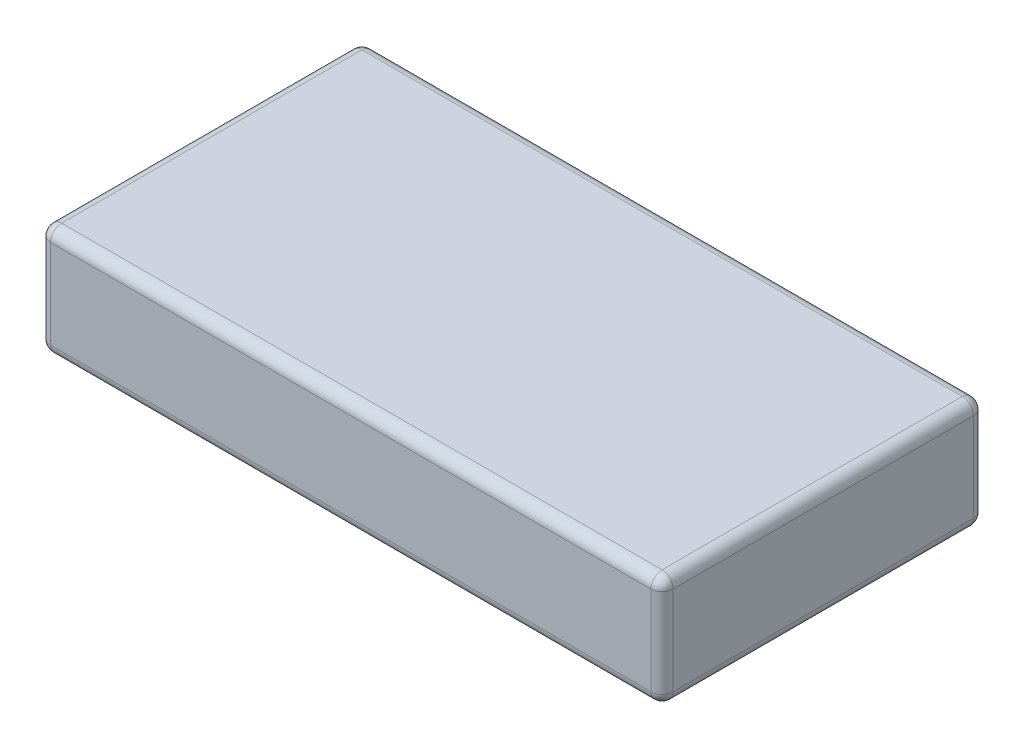
SolidWorks part; units mm, degrees
ref_plane "前视基准面" through (0, 0, 0) normal (0, 0, 1) x (1, 0, 0)
ref_plane "上视基准面" through (0, 0, 0) normal (0, 1, 0) x (1, 0, 0)
ref_plane "右视基准面" through (0, 0, 0) normal (1, 0, 0) x (0, 0, -1)
sketch "草图1" plane through (0, 0, 0) normal (0, 1, 0) x (1, 0, 0)
  line L1 (-28, 14.5) -> (28, 14.5)
  line L2 (-28, 14.5) -> (-28, -14.5)
  line L3 (-28, -14.5) -> (28, -14.5)
  line L4 (28, 14.5) -> (28, -14.5)
  line L5 (-28, 14.5) -> (28, -14.5) construction
  line L6 (-28, -14.5) -> (28, 14.5) construction
  point P1 (0, 0)
  dimension "D1" = 29
  dimension "D2" = 56
extrude "凸台-拉伸1" add sketch "草图1" along normal blind 10
fillet "圆角1" radius 1 12 edges at (-28, 5, -14.5) (28, 5, -14.5) (-28, 5, 14.5) (28, 5, 14.5) (0, 0, -14.5) (-28, 0, 0) (0, 0, 14.5) (28, 0, 0) (0, 10, 14.5) (-28, 10, 0) (0, 10, -14.5) (28, 10, 0)
